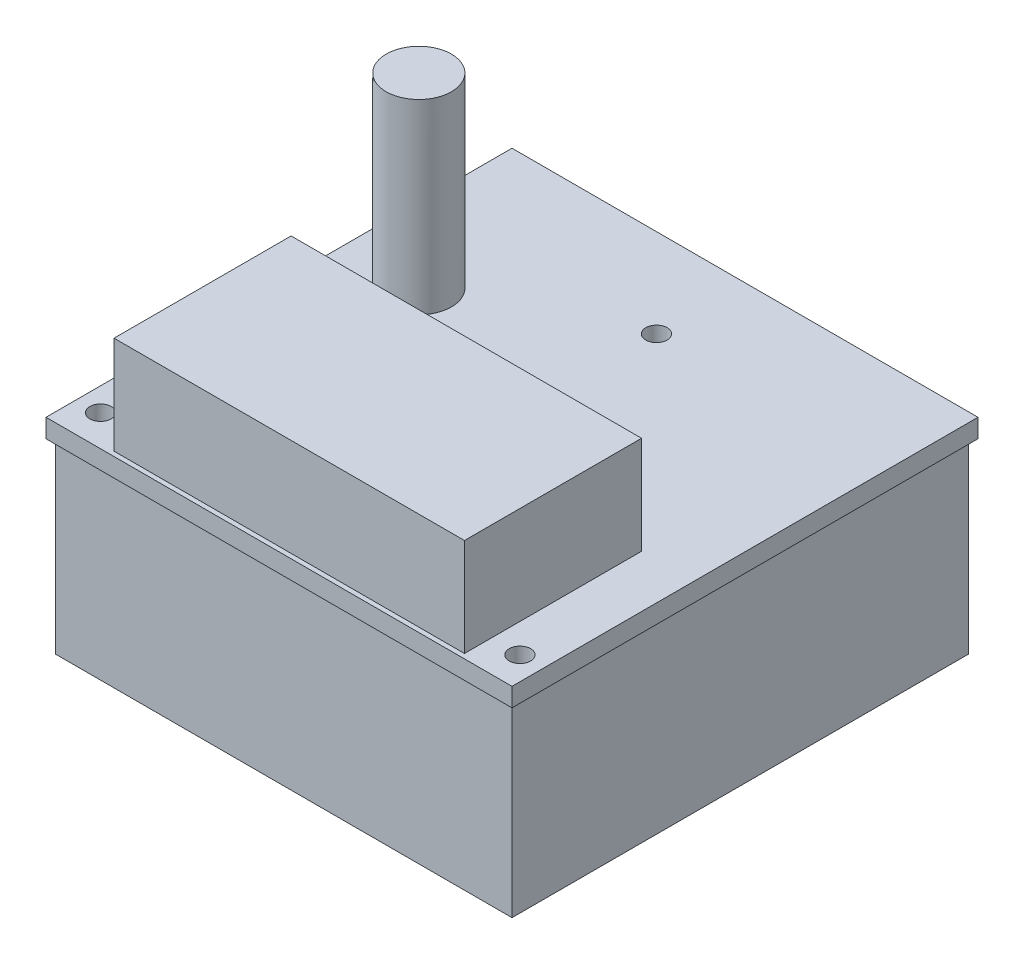
SolidWorks part; units mm, degrees
ref_plane "Front Plane" through (0, 0, 0) normal (0, 0, 1) x (1, 0, 0)
ref_plane "Top Plane" through (0, 0, 0) normal (0, 1, 0) x (1, 0, 0)
ref_plane "Right Plane" through (0, 0, 0) normal (1, 0, 0) x (0, 0, -1)
sketch "Sketch1" plane through (0, 0, 0) normal (0, 1, 0) x (1, 0, 0)
  line L1 (0, 0) -> (50, 0)
  line L2 (0, 0) -> (0, 50)
  line L3 (0, 50) -> (50, 50)
  line L4 (50, 0) -> (50, 50)
  circle A0 centre (2.5, 3.35) radius 1.15
  circle A1 centre (47.5, 3.35) radius 1.15
  circle A2 centre (25, 40.5) radius 1.15
  dimension "D3" = 2.3
  dimension "D4" = 2.3
  dimension "D5" = 2.3
  dimension "D6" = 3.35
  dimension "D7" = 2.5
  dimension "D8" = 3.35
  dimension "D9" = 2.5
  dimension "D10" = 9.5
  dimension "D11" = 25
  dimension "D1" = 50
  dimension "D2" = 50
extrude "Boss-Extrude1" add sketch "Sketch1" along normal blind 2
sketch "Sketch2" plane through (0, 2, 0) normal (0, 1, 0) x (1, 0, 0)
  line L0 (0, 50) -> (0, 0) construction
  line L1 (6.8, 0.5) -> (44.4, 0.5)
  line L2 (6.8, 0.5) -> (6.8, 19.5)
  line L3 (6.8, 19.5) -> (44.4, 19.5)
  line L4 (44.4, 0.5) -> (44.4, 19.5)
  line L5 (0, 0) -> (50, 0) construction
  dimension "D1" = 37.6
  dimension "D2" = 19
  dimension "D3" = 6.8
  dimension "D4" = 0.5
extrude "Boss-Extrude2" add sketch "Sketch2" along normal blind 10.5
sketch "Sketch3" plane through (0, 2, 0) normal (0, 1, 0) x (1, 0, 0)
  line L0 (50, 50) -> (0, 50) construction
  line L1 (0, 50) -> (0, 0) construction
  circle A0 centre (8, 32) radius 3.5
  dimension "D1" = 18
  dimension "D2" = 7
  dimension "D3" = 8
extrude "Boss-Extrude3" add sketch "Sketch3" along normal blind 20
sketch "Sketch4" plane through (0, 0, 0) normal (0, -1, 0) x (1, 0, 0)
  line L0 (0.5, -49.5) -> (49.5, -49.5)
  line L1 (49.5, -49.5) -> (49.5, -0.5)
  line L2 (49.5, -0.5) -> (0.5, -0.5)
  line L3 (0.5, -0.5) -> (0.5, -49.5)
extrude "Boss-Extrude4" add sketch "Sketch4" along normal blind 20
